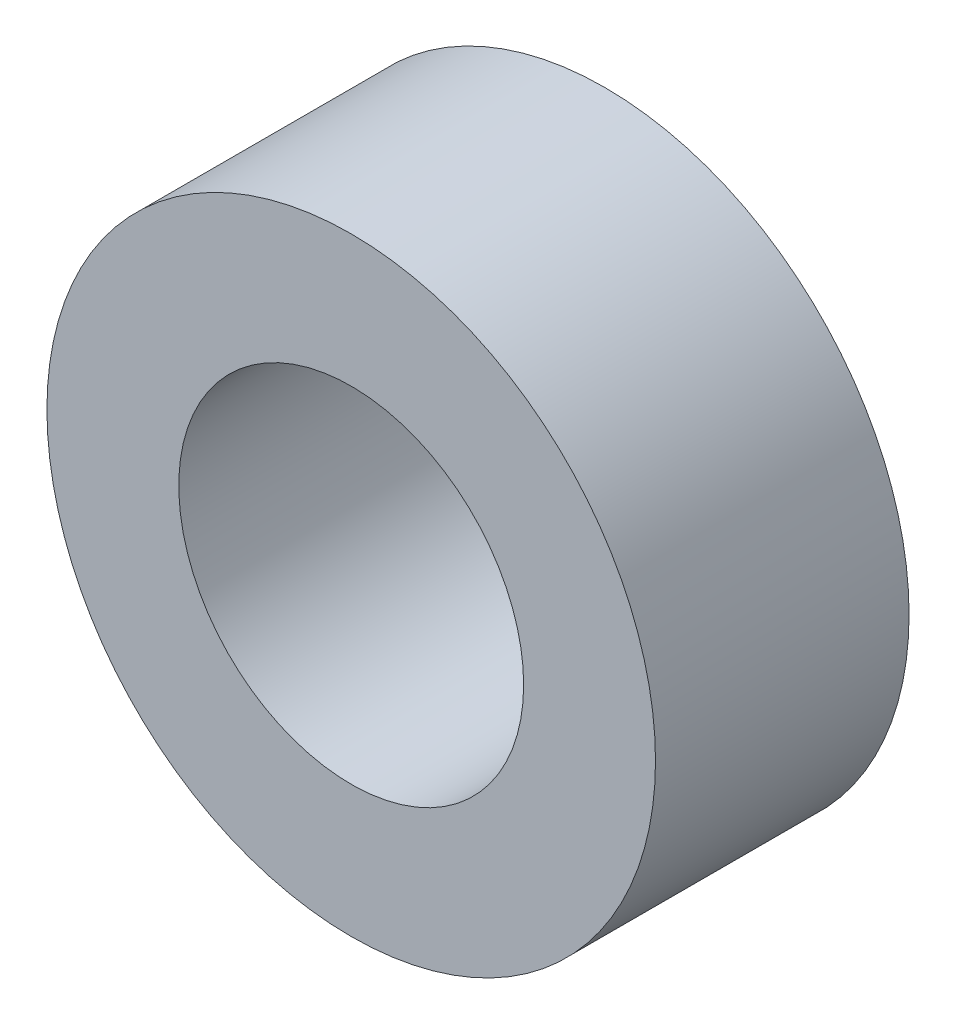
SolidWorks part; units mm, degrees
other "Limit and Lock Expander MCP23017 A Mount 1 Standoff"
ref_plane "Front Plane" through (0, 0, 0) normal (0, 0, 1) x (1, 0, 0)
ref_plane "Top Plane" through (0, 0, 0) normal (0, 1, 0) x (1, 0, 0)
ref_plane "Right Plane" through (0, 0, 0) normal (1, 0, 0) x (0, 0, -1)
sketch3d "Main Profile Sketch datum points"
  point P0 (0, 0, 96.5)
  point P1 (10, 0, 96.5)
  point P2 (0, 10, 96.5)
ref_plane "Main Profile Sketch plane" through (0, 0, 96.5) normal (0, 0, 1) x (1, 0, 0)
sketch "Main Profile Sketch" plane through (0, 0, 96.5) normal (0, 0, 1) x (1, 0, 0)
  circle A0 centre (188.5, -40.5) radius 3
  circle A1 centre (188.5, -40.5) radius 1.7
extrude "Main Extrusion" add sketch "Main Profile Sketch" against normal blind 2.5 separate body
